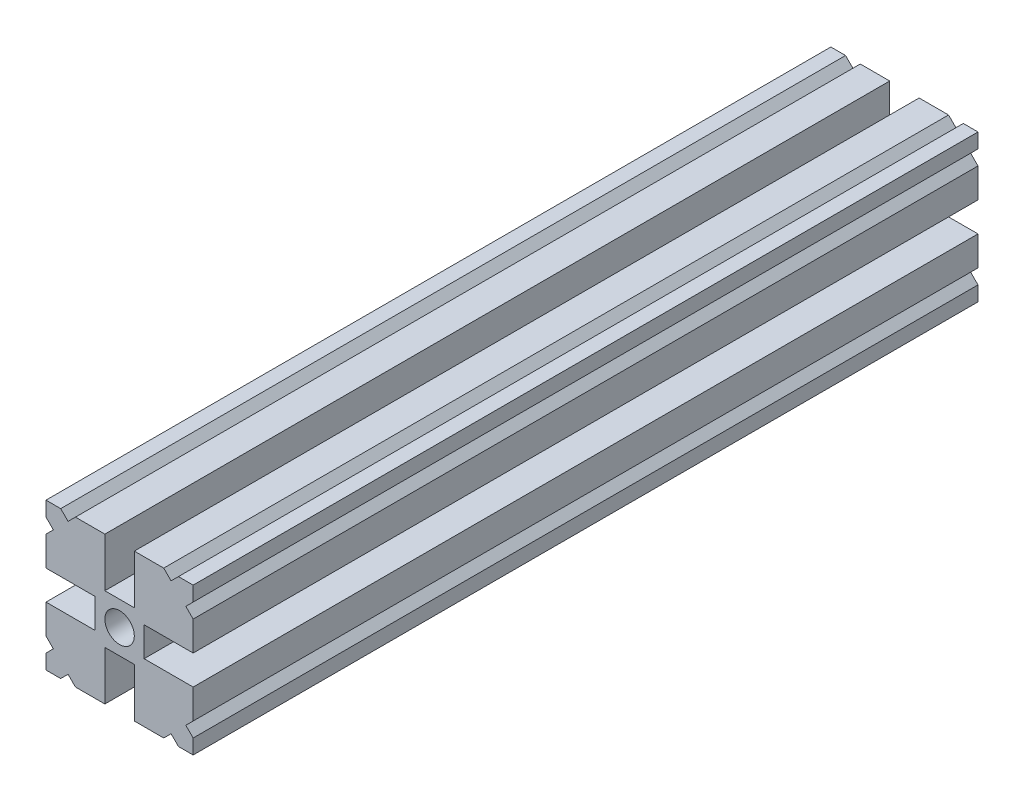
SolidWorks part; units mm, degrees
ref_plane "Front Plane" through (0, 0, 0) normal (0, 0, 1) x (1, 0, 0)
ref_plane "Top Plane" through (0, 0, 0) normal (0, 1, 0) x (1, 0, 0)
ref_plane "Right Plane" through (0, 0, 0) normal (1, 0, 0) x (0, 0, -1)
sketch "Sketch1" plane through (0, 0, 0) normal (0, 0, 1) x (1, 0, 0)
  line L0 (-1.5, 7.5) -> (1.5, 7.5) construction
  line L1 (-7.5, 7.5) -> (7.5, 7.5) construction
  line L2 (-7.5, 7.5) -> (-7.5, -7.5) construction
  line L3 (-7.5, -7.5) -> (7.5, -7.5) construction
  line L4 (7.5, 7.5) -> (7.5, -7.5) construction
  line L5 (-7.5, 7.5) -> (7.5, -7.5) construction
  line L6 (-7.5, -7.5) -> (7.5, 7.5) construction
  line L7 (-7.5, 7.5) -> (-6, 7.5)
  line L8 (7.5, 7.5) -> (6, 7.5)
  line L9 (-6, 7.5) -> (-5.25, 6.75)
  line L10 (-5.25, 6.75) -> (-4.5, 7.5)
  line L11 (-4.5, 7.5) -> (-1.5, 7.5)
  line L12 (-1.5, 7.5) -> (-1.5, 2.5)
  line L13 (-1.5, 2.5) -> (1.5, 2.5)
  line L14 (1.5, 2.5) -> (1.5, 7.5)
  line L15 (1.5, 7.5) -> (4.5, 7.5)
  line L16 (4.5, 7.5) -> (5.25, 6.75)
  line L17 (5.25, 6.75) -> (6, 7.5)
  line L18 (7.5, 7.5) -> (7.5, 6)
  line L19 (7.5, 6) -> (6.75, 5.25)
  line L20 (6.75, 5.25) -> (7.5, 4.5)
  line L21 (7.5, 4.5) -> (7.5, 1.5)
  line L22 (7.5, 1.5) -> (2.5, 1.5)
  line L23 (2.5, 1.5) -> (2.5, -1.5)
  line L24 (2.5, -1.5) -> (7.5, -1.5)
  line L25 (7.5, -1.5) -> (7.5, -4.5)
  line L26 (6.75, -5.25) -> (7.5, -6)
  line L27 (7.5, -4.5) -> (6.75, -5.25)
  line L28 (7.5, -7.5) -> (7.5, -6)
  line L29 (7.5, -7.5) -> (6, -7.5)
  line L30 (6, -7.5) -> (5.25, -6.75)
  line L31 (5.25, -6.75) -> (4.5, -7.5)
  line L32 (4.5, -7.5) -> (1.5, -7.5)
  line L33 (1.5, -7.5) -> (1.5, -2.5)
  line L34 (1.5, -2.5) -> (-1.5, -2.5)
  line L35 (-1.5, -2.5) -> (-1.5, -7.5)
  line L36 (-1.5, -7.5) -> (-4.5, -7.5)
  line L37 (-5.25, -6.75) -> (-6, -7.5)
  line L38 (-4.5, -7.5) -> (-5.25, -6.75)
  line L39 (-7.5, -7.5) -> (-6, -7.5)
  line L40 (-7.5, -7.5) -> (-7.5, -6)
  line L41 (-7.5, -6) -> (-6.75, -5.25)
  line L42 (-6.75, -5.25) -> (-7.5, -4.5)
  line L43 (-7.5, -4.5) -> (-7.5, -1.5)
  line L44 (-7.5, -1.5) -> (-2.5, -1.5)
  line L45 (-2.5, -1.5) -> (-2.5, 1.5)
  line L46 (-2.5, 1.5) -> (-7.5, 1.5)
  line L47 (-7.5, 1.5) -> (-7.5, 4.5)
  line L48 (-6.75, 5.25) -> (-7.5, 6)
  line L49 (-7.5, 4.5) -> (-6.75, 5.25)
  line L50 (-7.5, 7.5) -> (-7.5, 6)
  circle A0 centre (0, 0) radius 1.5
  point P0 (0, 0)
  point P8 (0, 7.5)
  point P56 (0, 0)
  dimension "D8" = 3
  dimension "D1" = 15
  dimension "D2" = 3
  dimension "D3" = 1.5
  dimension "D4" = 5
  dimension "D5" = 1.5
  dimension "D6" = 3
  dimension "D7" = 4
extrude "Boss-Extrude1" add sketch "Sketch1" along normal blind 80
